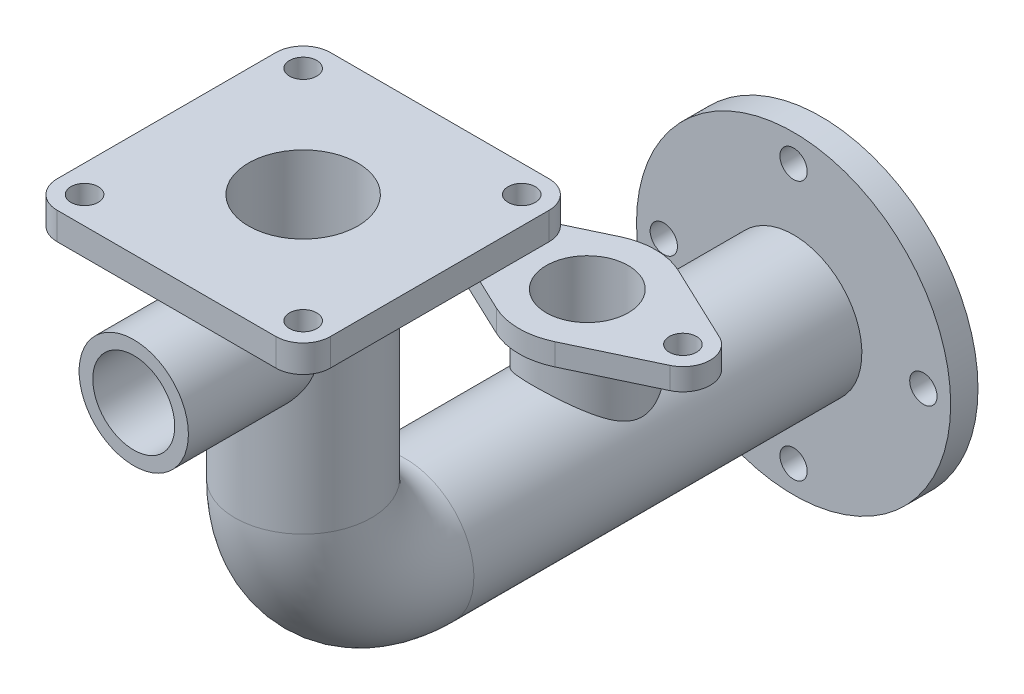
SolidWorks part; units mm, degrees
ref_plane "Front Plane" through (0, 0, 0) normal (0, 0, 1) x (1, 0, 0)
ref_plane "Top Plane" through (0, 0, 0) normal (0, 1, 0) x (1, 0, 0)
ref_plane "Right Plane" through (0, 0, 0) normal (1, 0, 0) x (0, 0, -1)
sketch "Sketch1" plane through (0, 0, 0) normal (0, 0, 1) x (1, 0, 0)
  circle A0 centre (0, 0) radius 12.5
  circle A1 centre (0, 0) radius 10
  dimension "D1" = 25
  dimension "D2" = 20
sketch "Sketch3" plane through (0, 0, 0) normal (1, 0, 0) x (0, 0, -1)
  line L0 (0, 0) -> (-76, 0)
  line L1 (-94.75, 18.75) -> (-94.75, 63.75)
  arc A0 (-76, 0) -> (-94.75, 18.75) centre (-76, 18.75) cw
  dimension "D3" = 18.75
  dimension "D1" = 76
  dimension "D2" = 45
sweep "Sweep1" add profiles "Sketch1" path "Sketch3"
sketch "Sketch9" plane through (0, 63.75, 0) normal (0, 1, 0) x (1, 0, 0)
  line L1 (-25, -69.75) -> (25, -69.75)
  line L2 (-25, -69.75) -> (-25, -119.75)
  line L3 (-25, -119.75) -> (25, -119.75)
  line L4 (25, -69.75) -> (25, -119.75)
  line L5 (-25, -69.75) -> (25, -119.75) construction
  line L6 (-25, -119.75) -> (25, -69.75) construction
  circle A0 centre (0, -94.75) radius 10 construction
  circle A1 centre (0, -94.75) radius 10
  point P0 (0, -94.75)
  dimension "D1" = 50
  dimension "D2" = 50
extrude "Boss-Extrude5" add sketch "Sketch9" against normal blind 5
fillet "Fillet1" radius 5 4 edges at (-25, 61.25, 119.75) (-25, 61.25, 69.75) (25, 61.25, 69.75) (25, 61.25, 119.75)
sketch "Sketch12" plane through (0, 63.75, 0) normal (0, 1, 0) x (1, 0, 0)
  point P0 (-20, -74.75)
  point P3 (20, -74.75)
  point P6 (20, -114.75)
  point P9 (-20, -114.75)
hole_wizard "Hole1" positions "Sketch12" profile "Sketch11" legacy
sketch "Sketch11" plane through (-20, 63.75, 74.75) normal (1, 0, 0) x (0, 0, 1)
  line L0 (0, 0) -> (0, 5)
  line L1 (0, 5) -> (2.5, 5)
  line L2 (2.5, 5) -> (2.5, 0)
  line L3 (2.5, 0) -> (0, 0)
  line L4 (0, 110) -> (0, -10) construction
  dimension "Diameter" = 5
  dimension "Depth" = 5
sketch "Sketch15" plane through (0, 0, 0) normal (0, 0, -1) x (-1, 0, 0)
  circle A0 centre (0, 0) radius 28.75
  circle A1 centre (0, 0) radius 10 construction
  circle A2 centre (0, 0) radius 10
  dimension "D1" = 57.5
extrude "Boss-Extrude7" add sketch "Sketch15" against normal blind 5
sketch "Sketch19" plane through (0, 0, 0) normal (0, 0, -1) x (-1, 0, 0)
  point P0 (23.75, 0)
  dimension "D1" = 23.75
hole_wizard "Hole2" positions "Sketch19" profile "Sketch18" legacy
sketch "Sketch18" plane through (-23.75, 0, 0) normal (1, 0, 0) x (0, 1, 0)
  line L0 (0, 0) -> (0, 5)
  line L1 (0, 5) -> (2.5, 5)
  line L2 (2.5, 5) -> (2.5, 0)
  line L3 (2.5, 0) -> (0, 0)
  line L4 (0, 110) -> (0, -10) construction
  dimension "Diameter" = 5
  dimension "Depth" = 5
pattern_circular "CirPattern2" count 4 over 360 about axis through (0, 0, 0) along (0, 0, 1) of "Hole2"
ref_plane "Plane1" through (0, 22.75, 0) normal (0, 1, 0) x (1, 0, 0)
sketch "Sketch20" plane through (0, 22.75, 0) normal (0, 1, 0) x (1, 0, 0)
  circle A0 centre (0, -42.75) radius 10
  point P2 (0, 0)
  point P4 (0, 0)
  point P5 (0, -42.75)
  point P6 (0, 0)
  point P7 (0, 0)
  dimension "D1" = 20
  dimension "D2" = 52
extrude "Boss-Extrude8" add sketch "Sketch20" against normal up to next
sketch "Sketch21" plane through (0, 22.75, 0) normal (0, 1, 0) x (1, 0, 0)
  line L0 (5.3571, -31.4562) -> (19.6429, -38.2325)
  line L1 (0, -42.75) -> (38.4248, -42.75) construction
  line L2 (5.3571, -54.0438) -> (19.6429, -47.2675)
  line L3 (0, -42.75) -> (0, -25.0002) construction
  line L4 (0, -25.0002) -> (0, -58.1862) construction
  line L5 (-5.3571, -54.0438) -> (-19.6429, -47.2675)
  line L6 (-5.3571, -31.4562) -> (-19.6429, -38.2325)
  arc A0 (-5.3571, -54.0438) -> (5.3571, -54.0438) centre (0, -42.75) ccw
  arc A1 (-19.6429, -38.2325) -> (-19.6429, -47.2675) centre (-17.5, -42.75) ccw
  arc A2 (19.6429, -47.2675) -> (19.6429, -38.2325) centre (17.5, -42.75) ccw
  arc A3 (5.3571, -31.4562) -> (-5.3571, -31.4562) centre (0, -42.75) ccw
  dimension "D1" = 25
  dimension "D2" = 10
  dimension "D3" = 17.5
extrude "Boss-Extrude9" add sketch "Sketch21" against normal blind 4 contours L0 A2 L2 A0 L5 A1 L6 A3
sketch "Sketch24" plane through (0, 22.75, 0) normal (0, 1, 0) x (1, 0, 0)
  point P0 (-17.5, -42.75)
  point P3 (17.5, -42.75)
hole_wizard "Hole3" positions "Sketch24" profile "Sketch23" legacy
sketch "Sketch23" plane through (-17.5, 22.75, 42.75) normal (1, 0, 0) x (0, 0, 1)
  line L0 (0, 0) -> (0, 5)
  line L1 (0, 5) -> (2.5, 5)
  line L2 (2.5, 5) -> (2.5, 0)
  line L3 (2.5, 0) -> (0, 0)
  line L4 (0, 110) -> (0, -10) construction
  dimension "Diameter" = 5
  dimension "Depth" = 5
sketch "Sketch31" plane through (0, 22.75, 0) normal (0, 1, 0) x (1, 0, 0)
  point P0 (0, -42.75)
hole_wizard "Hole5" positions "Sketch31" profile "Sketch30" legacy
sketch "Sketch30" plane through (0, 22.75, 42.75) normal (1, 0, 0) x (0, 0, 1)
  line L0 (0, 0) -> (0, 22.75)
  line L1 (0, 22.75) -> (7.5, 22.75)
  line L2 (7.5, 22.75) -> (7.5, 0)
  line L3 (7.5, 0) -> (0, 0)
  line L4 (0, 110) -> (0, -10) construction
  dimension "Diameter" = 15
  dimension "Depth" = 22.75
ref_plane "Plane3" through (0, 0, 125.75) normal (0, 0, 1) x (1, 0, 0)
sketch "Sketch32" plane through (0, 0, 125.75) normal (0, 0, 1) x (1, 0, 0)
  circle A0 centre (0, 46.25) radius 10
  dimension "D1" = 20
  dimension "D2" = 46.25
extrude "Boss-Extrude10" add sketch "Sketch32" against normal up to next
sketch "Sketch36" plane through (0, 0, 125.75) normal (0, 0, 1) x (1, 0, 0)
  point P0 (0, 46.25)
hole_wizard "Hole6" positions "Sketch36" profile "Sketch35" legacy
sketch "Sketch35" plane through (0, 46.25, 125.75) normal (1, 0, 0) x (0, -1, 0)
  line L0 (0, 0) -> (0, 21)
  line L1 (0, 21) -> (7.5, 21)
  line L2 (7.5, 21) -> (7.5, 0)
  line L3 (7.5, 0) -> (0, 0)
  line L4 (0, 110) -> (0, -10) construction
  dimension "Diameter" = 15
  dimension "Depth" = 21
